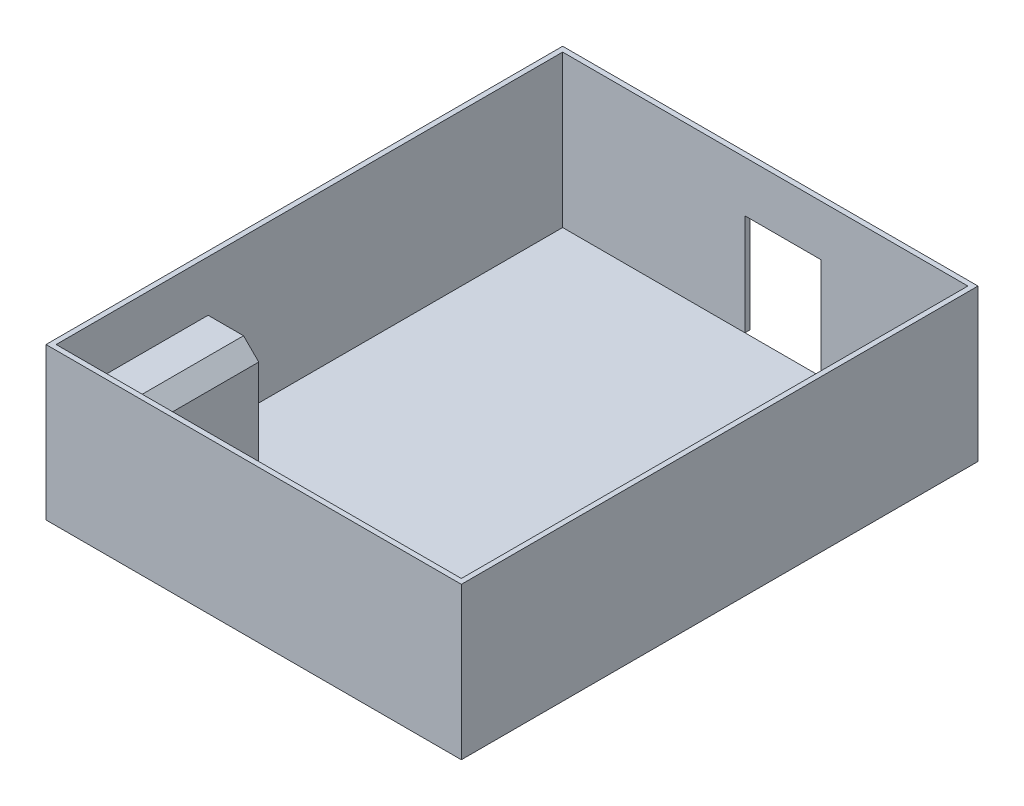
SolidWorks part; units mm, degrees
ref_plane "Front" through (0, 0, 0) normal (0, 0, 1) x (1, 0, 0)
ref_plane "Top" through (0, 0, 0) normal (0, 1, 0) x (1, 0, 0)
ref_plane "Right" through (0, 0, 0) normal (1, 0, 0) x (0, 0, -1)
sketch "Sketch1" plane through (0, 0, 0) normal (0, 1, 0) x (1, 0, 0)
  line L1 (0, 0) -> (-8000, 0)
  line L2 (0, 0) -> (0, 10000)
  line L3 (0, 10000) -> (-8000, 10000)
  line L4 (-8000, 0) -> (-8000, 10000)
  dimension "D1" = 8000
  dimension "D2" = 10000
extrude "Boss-Extrude1" add sketch "Sketch1" along normal blind 10
sketch "Sketch3" plane through (0, 10, 0) normal (0, 1, 0) x (1, 0, 0)
  line L0 (100, -100) -> (100, 10100)
  line L1 (100, 10100) -> (-8100, 10100)
  line L2 (-8100, 10100) -> (-8100, -100)
  line L3 (-8100, -100) -> (100, -100)
  line L4 (0, 0) -> (0, 10000)
  line L5 (0, 10000) -> (-8000, 10000)
  line L6 (-8000, 10000) -> (-8000, 0)
  line L7 (-8000, 0) -> (0, 0)
  line L8 (0, 0) -> (0, 10000)
  line L9 (0, 10000) -> (-8000, 10000)
  line L10 (-8000, 10000) -> (-8000, 0)
  line L11 (-8000, 0) -> (0, 0)
  dimension "D1" = 0
  dimension "D2" = 100
extrude "Boss-Extrude2" add sketch "Sketch3" along normal blind 3000 separate body
sketch "Sketch4" plane through (0, 0, -10100) normal (0, 0, -1) x (-1, 0, 0)
  line L0 (-100, 10) -> (8100, 10) construction
  line L1 (4400, 10) -> (2900, 10)
  line L2 (4400, 10) -> (4400, 2010)
  line L3 (4400, 2010) -> (2900, 2010)
  line L4 (2900, 10) -> (2900, 2010)
  line L5 (-100, 3010) -> (-100, 10) construction
  dimension "D1" = 3000
  dimension "D2" = 2000
  dimension "D3" = 1500
extrude "Cut-Extrude1" cut sketch "Sketch4" against normal blind 100
sketch "Sketch5" plane through (0, 10, 0) normal (0, 1, 0) x (1, 0, 0)
  line L1 (-8000, 0) -> (-7000, 0)
  line L2 (-8000, 0) -> (-8000, 3000)
  line L3 (-8000, 3000) -> (-7000, 3000)
  line L4 (-7000, 0) -> (-7000, 3000)
  dimension "D1" = 1000
  dimension "D2" = 3000
extrude "Boss-Extrude4" add sketch "Sketch5" along normal blind 2000 separate body
chamfer "Chamfer1" distance 300 angle 45 1 edges at (-7000, 2010, -1500)
